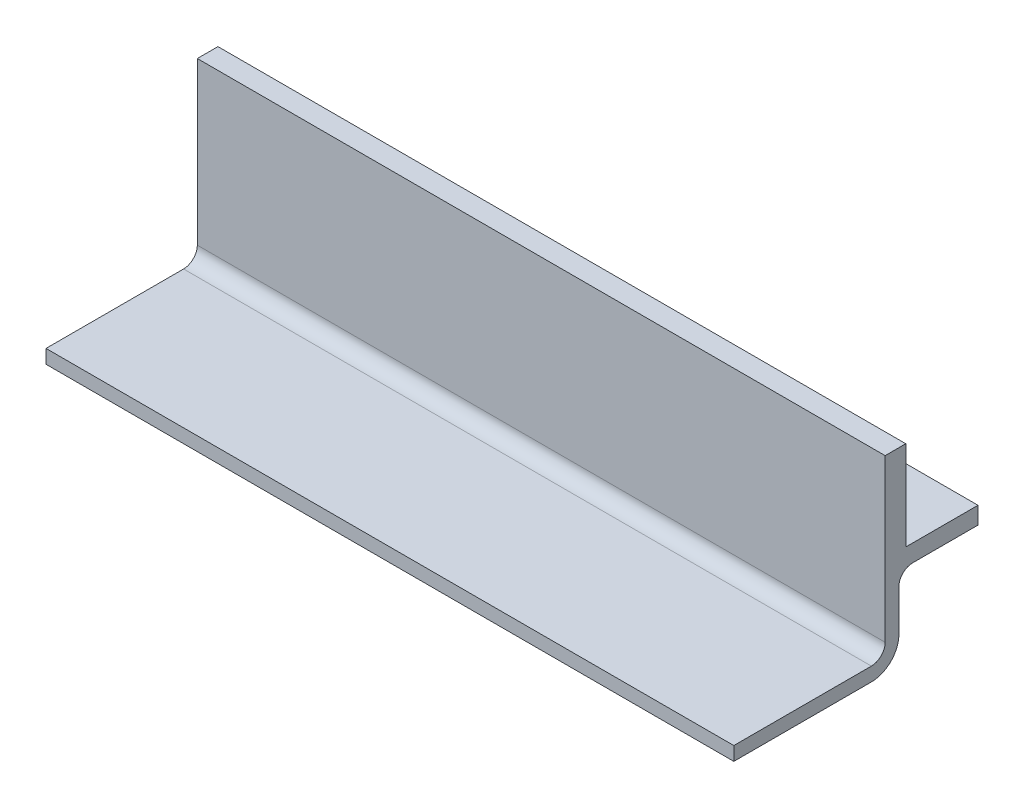
SolidWorks part; units mm, degrees
ref_plane "Piano frontale" through (0, 0, 0) normal (0, 0, 1) x (1, 0, 0)
ref_plane "Piano superiore" through (0, 0, 0) normal (0, 1, 0) x (1, 0, 0)
ref_plane "Piano destro" through (0, 0, 0) normal (1, 0, 0) x (0, 0, -1)
ref_plane "Piano1" through (0, -9.5, 0) normal (0, 1, 0) x (1, 0, 0)
sketch "Schizzo1" plane through (0, -9.5, 0) normal (0, 1, 0) x (1, 0, 0)
  line L0 (0, -10) -> (0, -45.5)
  line L1 (0, -45.5) -> (100, -45.5)
  line L2 (100, -45.5) -> (100, -10)
  line L3 (100, -10) -> (0, -10)
  dimension "D1" = 100
  dimension "D2" = 35.5
extrude "Estrusione-Estrusione1" add sketch "Schizzo1" against normal blind 27.5
sketch "Schizzo2" plane through (0, 0, 0) normal (-1, 0, 0) x (0, 0, 1)
  line L0 (21.5, -25) -> (10, -25)
  line L1 (10, -25) -> (10, -37)
  line L2 (10, -37) -> (21.5, -37)
  line L3 (21.5, -37) -> (21.5, -25)
  line L4 (10, -9.5) -> (45.5, -9.5) construction
  dimension "D1" = 11.5
  dimension "D2" = 15.5
  dimension "D3" = 27.5
extrude "Taglio-Estrusione1" cut sketch "Schizzo2" against normal through all
sketch "Schizzo3" plane through (0, 0, 0) normal (-1, 0, 0) x (0, 0, 1)
  line L0 (20.5, -22.5) -> (20.5, -9.5)
  line L1 (20.5, -9.5) -> (10, -9.5)
  line L2 (10, -9.5) -> (10, -22.5)
  line L3 (10, -22.5) -> (20.5, -22.5)
  line L4 (45.5, -37) -> (45.5, -9.5) construction
  line L5 (21.5, -37) -> (45.5, -37) construction
  dimension "D1" = 25
  dimension "D2" = 35.5
  dimension "D3" = 14.5
  dimension "D4" = 27.5
extrude "Taglio-Estrusione2" cut sketch "Schizzo3" against normal through all
sketch "Schizzo4" plane through (0, 0, 0) normal (-1, 0, 0) x (0, 0, 1)
  line L0 (23.5, -35) -> (45.5, -35)
  line L1 (45.5, -35) -> (45.5, -9.5)
  line L2 (45.5, -9.5) -> (23.5, -9.5)
  line L3 (23.5, -9.5) -> (23.5, -35)
  line L4 (10, -25) -> (10, -22.5) construction
  line L5 (10, -22.5) -> (20.5, -22.5) construction
  dimension "D1" = 13.5
  dimension "D2" = 35.5
  dimension "D3" = 13
  dimension "D4" = 12.5
extrude "Taglio-Estrusione3" cut sketch "Schizzo4" against normal through all
hole_wizard "Foro svasato per Vite M3.5-1" positions "Schizzo6" profile "Schizzo5" countersink size "M3.5" standard "Ansi Metric"
sketch "Schizzo6" plane through (0, -25, 0) normal (0, -1, 0) x (-1, 0, 0)
  point P0 (-15, -14.5)
  point P1 (-85, -14.5)
sketch "Schizzo5" plane through (15, -25, 14.5) normal (1, 0, 0) x (0, 0, -1)
  line L0 (0, 0) -> (0, 15.5)
  line L1 (0, 15.5) -> (2, 15.5)
  line L2 (2, 15.5) -> (2, 1.3)
  line L3 (2, 1.3) -> (3.3, 0)
  line L5 (3.3, 0) -> (0, 0)
  line L6 (-2, 1.3) -> (-3.3, 0) construction
  line L11 (0, -6.35) -> (0, 107.95) construction
  dimension "Thru Hole Dia." = 4
  dimension "Thru Hole Depth" = 15.5
  dimension "Near C'Sink Dia." = 6.6
  dimension "Near C'Sink Angle" = 90
fillet "Raccordo1" radius 2 2 edges at (50, -35, 23.5) (50, -25, 21.5)
fillet "Raccordo2" radius 4 1 edges at (50, -37, 21.5)
